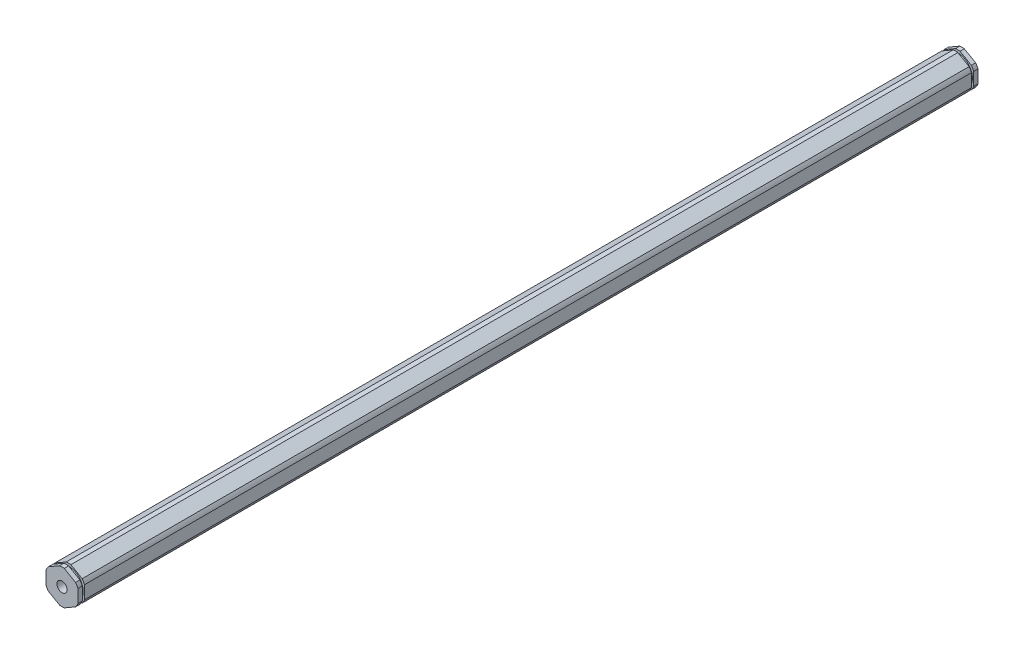
SolidWorks part; units mm, degrees
ref_plane "Front Plane" through (0, 0, 0) normal (0, 0, 1) x (1, 0, 0)
ref_plane "Top Plane" through (0, 0, 0) normal (0, 1, 0) x (1, 0, 0)
ref_plane "Right Plane" through (0, 0, 0) normal (1, 0, 0) x (0, 0, -1)
sketch "Sketch1" plane through (0, 0, 0) normal (0, 0, 1) x (1, 0, 0)
  line L1 (0, 7.3323) -> (-6.35, 3.6662)
  line L2 (-6.35, 3.6662) -> (-6.35, -3.6662)
  line L3 (-6.35, -3.6662) -> (0, -7.3323)
  line L4 (0, -7.3323) -> (6.35, -3.6662)
  line L5 (6.35, -3.6662) -> (6.35, 3.6662)
  line L6 (6.35, 3.6662) -> (0, 7.3323)
  circle A0 centre (0, 0) radius 6.35 construction
  circle A1 centre (0, 0) radius 6.858
  dimension "D1" = 12.7
  dimension "D2" = 13.716
extrude "Boss-Extrude1" add sketch "Sketch1" along normal mid plane 357.759 contours L5 A1 L6 L1 L2 L3 L4
hole_wizard "#10-32 Tapped Hole1" positions "3DSketch1" profile "Sketch2" tap size "#10-32" standard "ANSI Inch"
sketch3d "3DSketch1"
  line L0 (0, 0, 178.8795) -> (0, 0, -178.8795) construction
  line L1 (0, 0, 178.8795) -> (0, 0, -178.8795) construction
  point P0 (0, 0, 178.8795)
  point P4 (0, 0, -178.8795)
sketch "Sketch2" plane through (0, 0, 178.8795) normal (1, 0, 0) x (0, -1, 0)
  line L0 (0, 0) -> (0, 17.5608)
  line L1 (0, 17.5608) -> (2.0193, 16.3474)
  line L2 (2.0193, 16.3474) -> (2.0193, 0)
  line L5 (2.0193, 0) -> (0, 0)
  line L10 (0, 17.5608) -> (-2.0193, 16.3474) construction
  line L11 (0, -6.35) -> (0, 107.95) construction
  dimension "Tap Drill Dia." = 4.0386
  dimension "Tap Drill Depth" = 16.3474
  dimension "Drill Angle" = 118
cosmetic thread "Hole Thread1" parameters "D1"=13.97, "D2"=4.826
cosmetic thread "Hole Thread2" parameters "D1"=13.97, "D2"=4.826
sketch "Sketch5" plane through (0, 0, 0) normal (1, 0, 0) x (0, 0, -1)
  line L0 (178.8795, 6.858) -> (-178.8795, 6.858) construction
  line L1 (-177.165, 6.858) -> (-176.276, 6.858)
  line L2 (-177.165, 6.858) -> (-177.165, 5.8547)
  line L3 (-177.165, 5.8547) -> (-176.276, 5.8547)
  line L4 (-176.276, 6.858) -> (-176.276, 5.8547)
  line L5 (-165.0472, 0) -> (-158.8423, 0) construction
  dimension "D1" = 5.8547
  dimension "D2" = 0.889
  dimension "D3" = 1.7145
revolve "Cut-Revolve1" cut sketch "Sketch5" angle 360 about L5
mirror "Mirror1" about plane through (0, 0, 0) normal (0, 0, 1) of "Cut-Revolve1"
